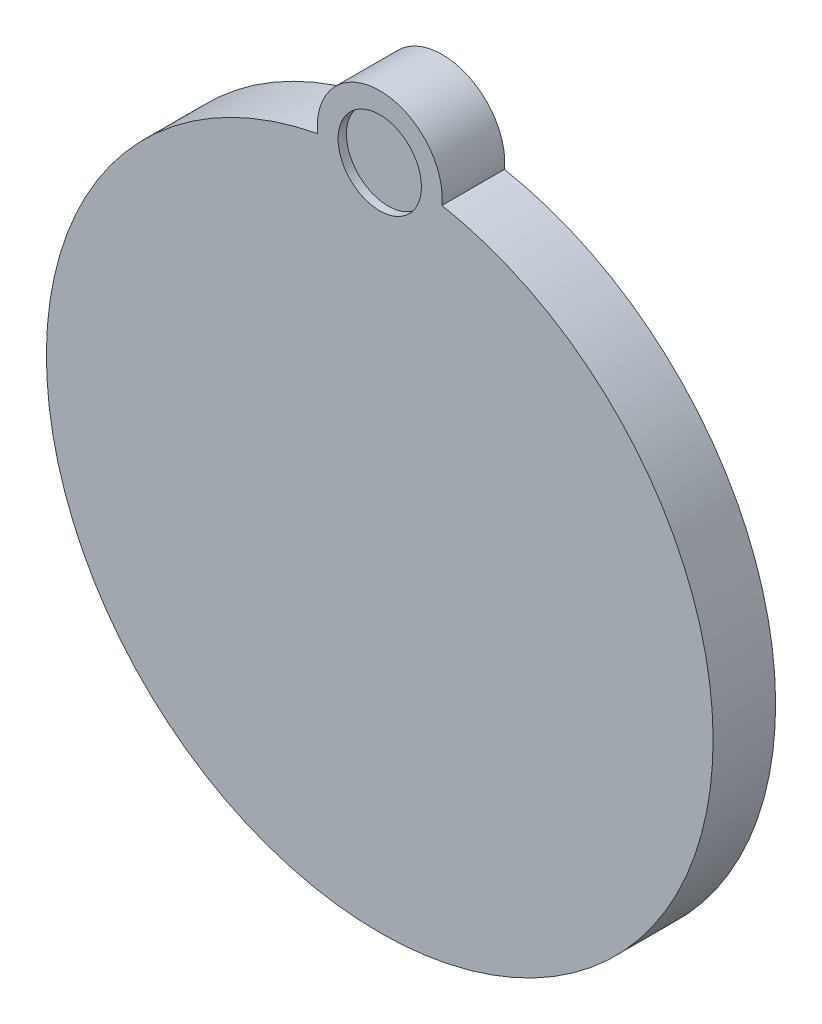
SolidWorks part; units mm, degrees
ref_plane "正面" through (0, 0, 0) normal (0, 0, 1) x (1, 0, 0)
ref_plane "平面" through (0, 0, 0) normal (0, 1, 0) x (1, 0, 0)
ref_plane "右側面" through (0, 0, 0) normal (1, 0, 0) x (0, 0, -1)
sketch "ｽｹｯﾁ4" plane through (0, 0, 0) normal (0, 0, 1) x (1, 0, 0)
  arc A1 (-14.9339, -1.4063) -> (9.9804, -0.625) centre (0, -80) ccw
  arc A3 (14.9339, -1.4063) -> (-14.9339, -1.4063) centre (0, 0) ccw
  dimension "D4" = 30
  dimension "D2" = 80
extrude "ﾎﾞｽ - 押し出し1" add sketch "ｽｹｯﾁ4" along normal blind 15
sketch "ｽｹｯﾁ10" plane through (0, 0, 15) normal (0, 0, 1) x (1, 0, 0)
  circle A0 centre (0, 0) radius 10
  dimension "D1" = 20
extrude "ｶｯﾄ - 押し出し3" cut sketch "ｽｹｯﾁ10" against normal blind 2
